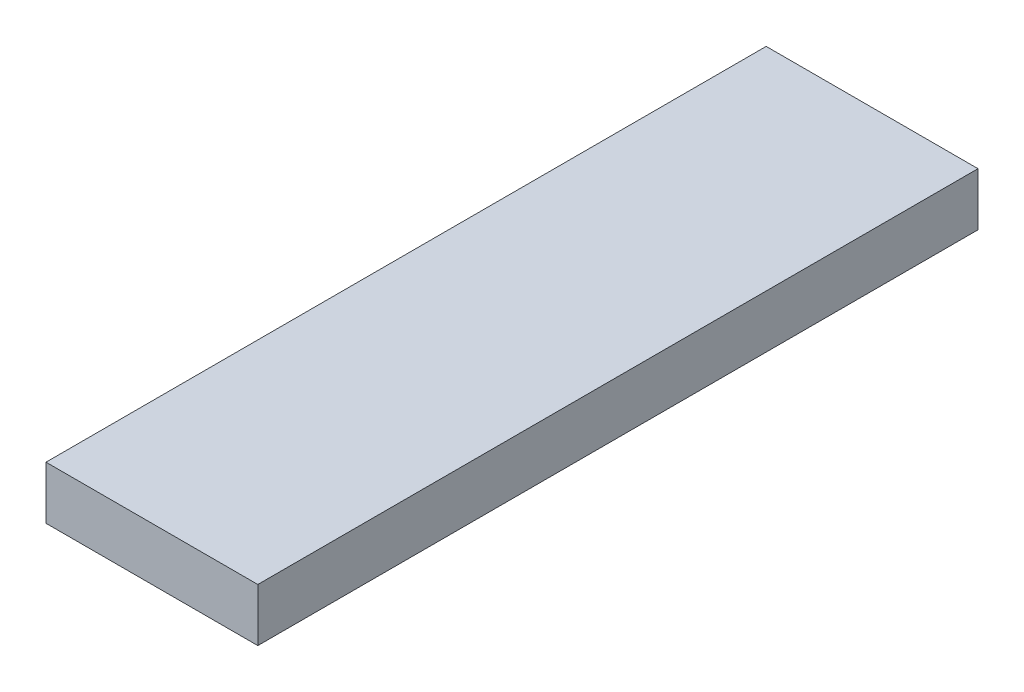
SolidWorks part; units mm, degrees
ref_plane "Front Plane" through (0, 0, 0) normal (0, 0, 1) x (1, 0, 0)
ref_plane "Top Plane" through (0, 0, 0) normal (0, 1, 0) x (1, 0, 0)
ref_plane "Right Plane" through (0, 0, 0) normal (1, 0, 0) x (0, 0, -1)
sketch "Sketch1" plane through (0, 0, 0) normal (0, 1, 0) x (1, 0, 0)
  line L1 (-6.1159, -24.4269) -> (6.5841, -24.4269)
  line L2 (-6.1159, -24.4269) -> (-6.1159, 18.7531)
  line L3 (-6.1159, 18.7531) -> (6.5841, 18.7531)
  line L4 (6.5841, -24.4269) -> (6.5841, 18.7531)
  line L5 (-6.1159, -24.4269) -> (6.5841, 18.7531) construction
  line L6 (-6.1159, 18.7531) -> (6.5841, -24.4269) construction
  point P0 (0.2341, -2.8369)
  dimension "D1" = 43.18
  dimension "D2" = 12.7
extrude "Boss-Extrude1" add sketch "Sketch1" along normal blind 3.175
